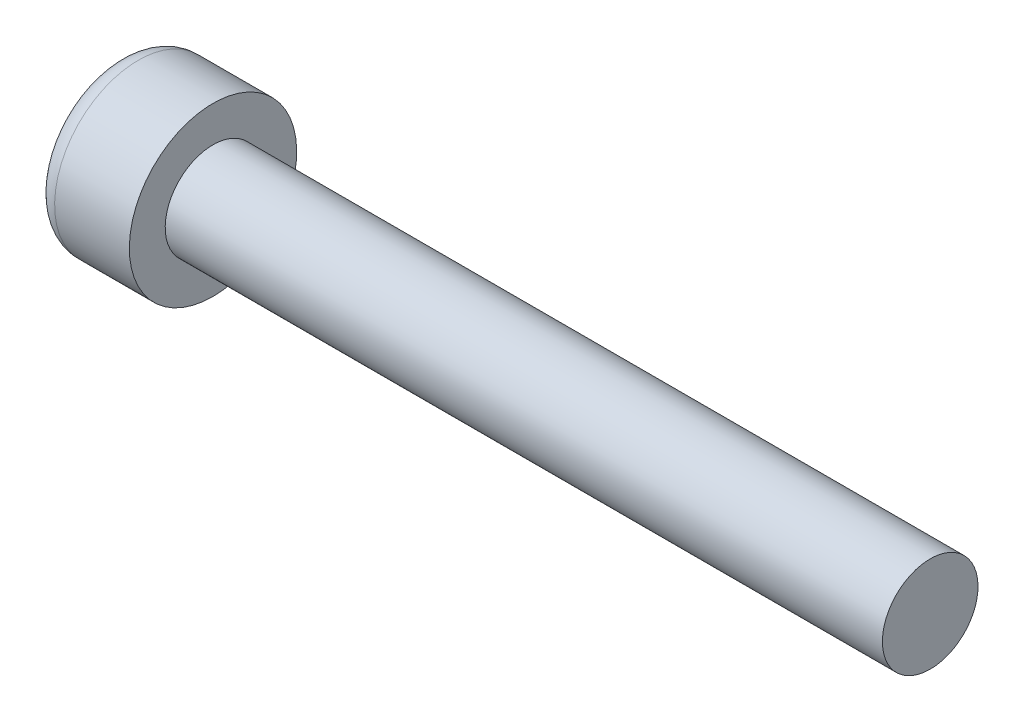
SolidWorks part; units mm, degrees
material "Plain Carbon Steel"
ref_plane "Front Plane" through (0, 0, 0) normal (0, 0, 1) x (1, 0, 0)
ref_plane "Top Plane" through (0, 0, 0) normal (0, 1, 0) x (1, 0, 0)
ref_plane "Right Plane" through (0, 0, 0) normal (1, 0, 0) x (0, 0, -1)
sketch "Sketch1" plane through (0, 0, 0) normal (0, 0, 1) x (1, 0, 0)
  line L0 (0, 0) -> (0, 2.625)
  line L1 (0.875, 3.5) -> (4, 3.5)
  line L2 (4, 3.5) -> (4, 2)
  line L3 (4, 2) -> (34, 2)
  line L4 (34, 2) -> (34, 0)
  line L5 (34, 0) -> (0, 0) construction
  line L6 (0.875, 2.625) -> (0.875, 1.75) construction
  line L7 (0.875, 1.75) -> (0.875, 0.875) construction
  line L8 (0.875, 0.875) -> (0.875, 0) construction
  line L9 (0.875, 3.5) -> (0.875, 2.625) construction
  line L10 (0, 0) -> (34, 0)
  arc A0 (0, 2.625) -> (0.875, 3.5) centre (0.875, 2.625) cw
  dimension "D1" = 4
  dimension "D2" = 7
  dimension "D3" = 4
  dimension "D4" = 30
revolve "Revolve1" add sketch "Sketch1" angle 360 about L10
sketch "Sketch2" plane through (0, 0, 0) normal (-1, 0, 0) x (0, 0, 1)
  line L1 (0, 1.7321) -> (-1.5, 0.866)
  line L2 (-1.5, 0.866) -> (-1.5, -0.866)
  line L3 (-1.5, -0.866) -> (0, -1.7321)
  line L4 (0, -1.7321) -> (1.5, -0.866)
  line L5 (1.5, -0.866) -> (1.5, 0.866)
  line L6 (1.5, 0.866) -> (0, 1.7321)
  circle A0 centre (0, 0) radius 1.5 construction
  dimension "D1" = 3
extrude "Cut-Extrude1" cut sketch "Sketch2" against normal blind 2
